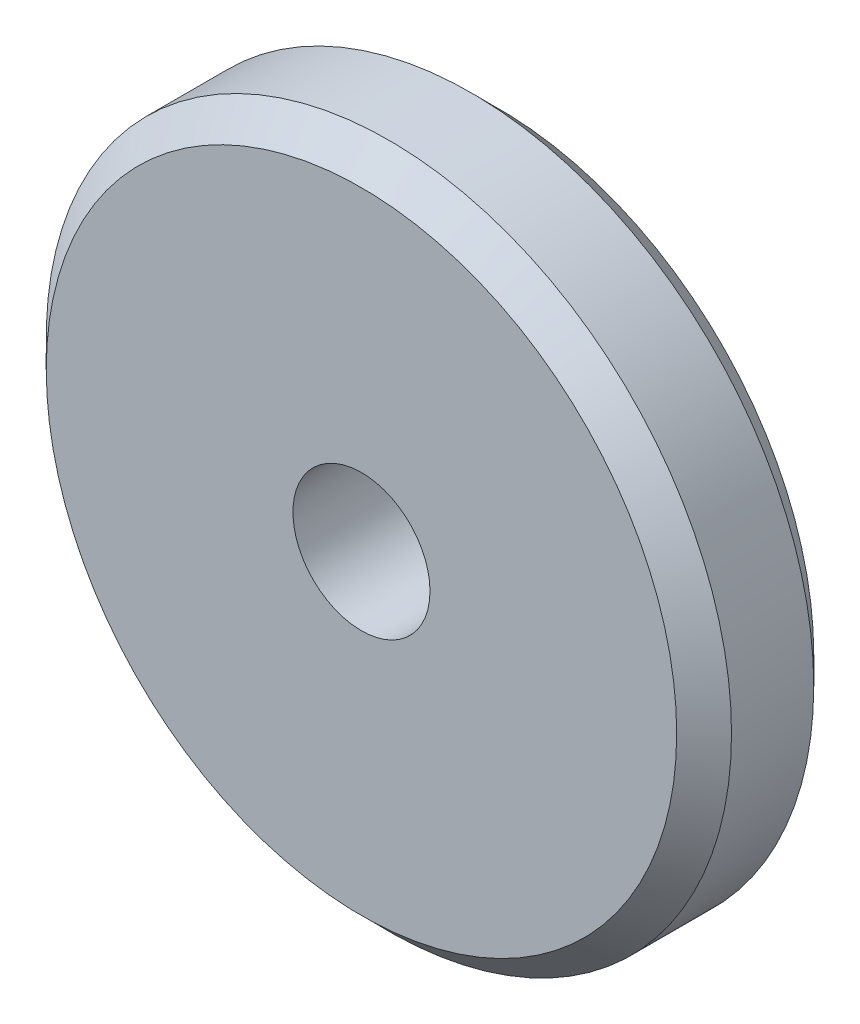
SolidWorks part; units mm, degrees
material "AISI 316 Stainless Steel Sheet (SS)"
ref_plane "Front Plane" through (0, 0, 0) normal (0, 0, 1) x (1, 0, 0)
ref_plane "Top Plane" through (0, 0, 0) normal (0, 1, 0) x (1, 0, 0)
ref_plane "Right Plane" through (0, 0, 0) normal (1, 0, 0) x (0, 0, -1)
sketch "Sketch1" plane through (0, 0, 0) normal (0, 0, 1) x (1, 0, 0)
  circle A0 centre (0, 0) radius 25
  circle A1 centre (0, 0) radius 5
  dimension "D1" = 10
  dimension "D2" = 50
extrude "Boss-Extrude1" add sketch "Sketch1" along normal blind 10
chamfer "Chamfer1" distance 2 angle 45 2 edges at (25, 0, 0) (25, 0, 10)
ref_point "Point1"
